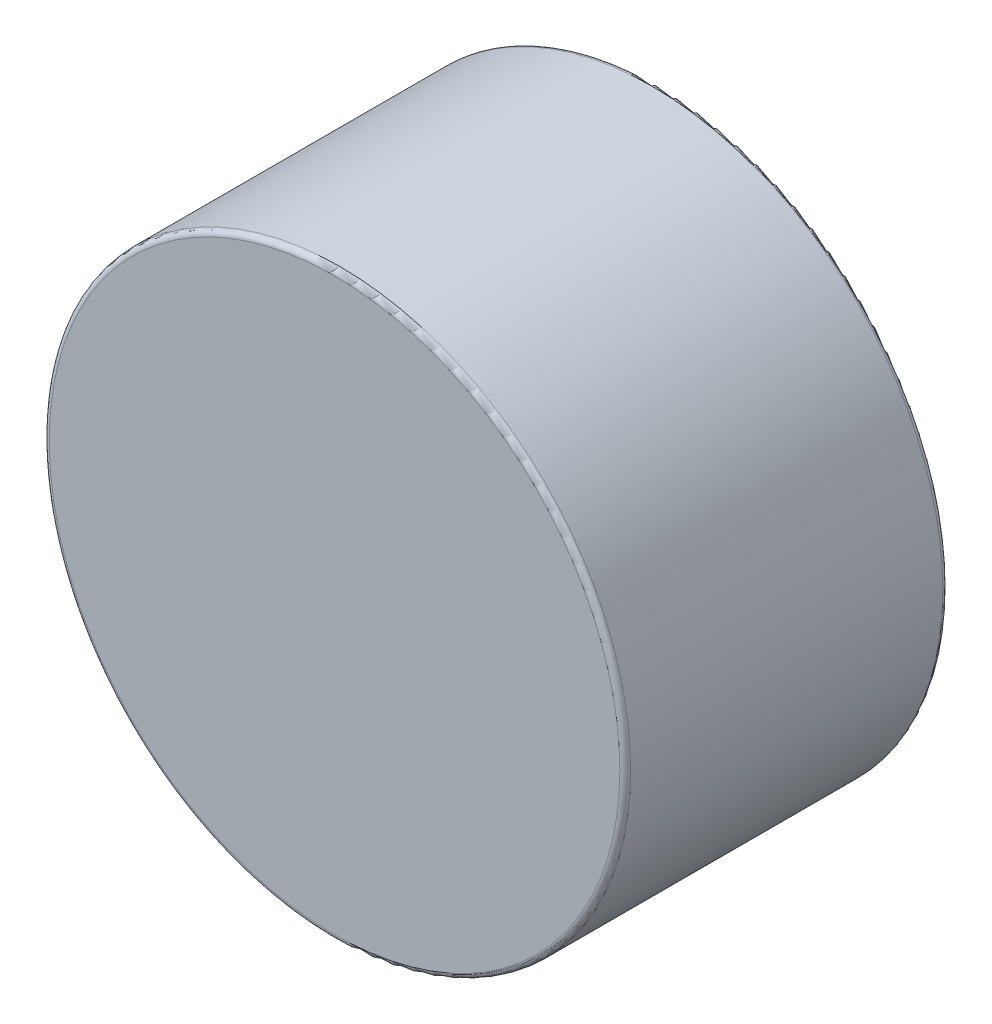
SolidWorks part; units mm, degrees
material "AISI 1020"
ref_plane "Front Plane" through (0, 0, 0) normal (0, 0, 1) x (1, 0, 0)
ref_plane "Top Plane" through (0, 0, 0) normal (0, 1, 0) x (1, 0, 0)
ref_plane "Right Plane" through (0, 0, 0) normal (1, 0, 0) x (0, 0, -1)
sketch "Sketch1" plane through (0, 0, 0) normal (0, 0, 1) x (1, 0, 0)
  circle A0 centre (0, 0) radius 27
  dimension "D1" = 54
extrude "Boss-Extrude1" add sketch "Sketch1" along normal mid plane 30
fillet "Fillet1" radius 0.5 2 edges at (27, 0, -15) (27, 0, 15)
